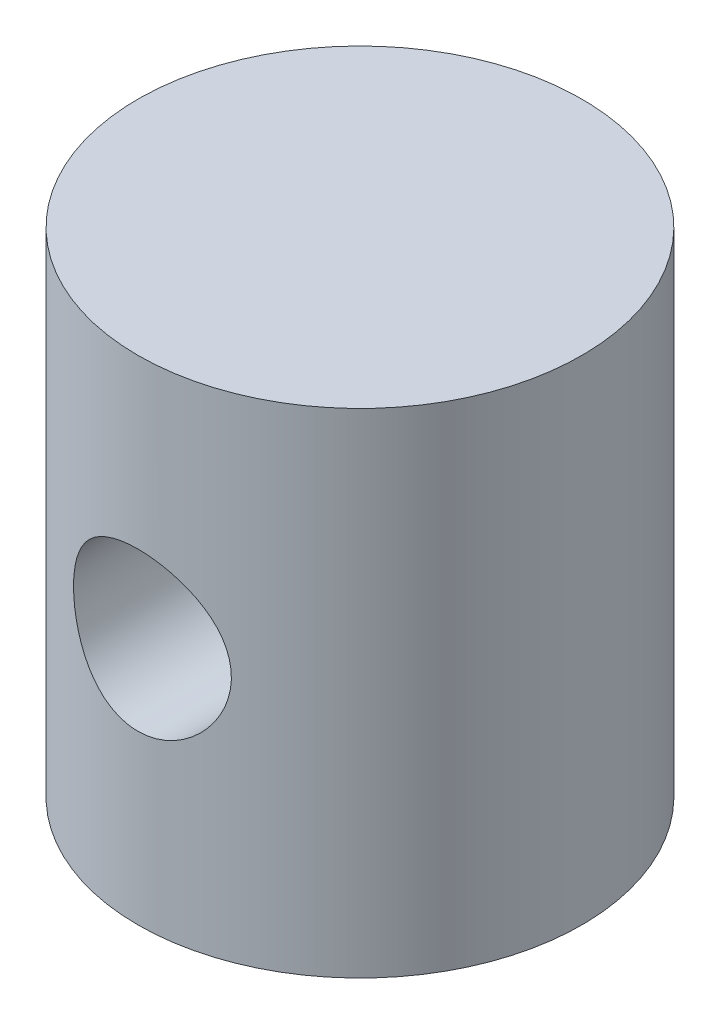
SolidWorks part; units mm, degrees
ref_plane "Front Plane" through (0, 0, 0) normal (0, 0, 1) x (1, 0, 0)
ref_plane "Top Plane" through (0, 0, 0) normal (0, 1, 0) x (1, 0, 0)
ref_plane "Right Plane" through (0, 0, 0) normal (1, 0, 0) x (0, 0, -1)
sketch "Sketch3" plane through (0, 0, 0) normal (0, 1, 0) x (1, 0, 0)
  circle A0 centre (0, 0) radius 4.5
  dimension "D1" = 9
extrude "Boss-Extrude1" add sketch "Sketch3" along normal blind 10
sketch "Sketch4" plane through (0, 0, 0) normal (0, 0, 1) x (1, 0, 0)
  line L0 (-4.5, 5) -> (-1.6, 5)
  line L1 (-4.5, 10) -> (-4.5, 0) construction
  line L2 (4.5, 0) -> (4.5, 10) construction
  line L3 (1.6, 5) -> (4.5, 5)
  circle A0 centre (0, 5) radius 1.6
  dimension "D1" = 3.2
extrude "Cut-Extrude1" cut sketch "Sketch4" against normal blind 10 contours A0
sketch "Sketch9" plane through (0, 0, 0) normal (0, 0, 1) x (1, 0, 0)
  circle A0 centre (0, 5) radius 1.6
extrude "Cut-Extrude2" cut sketch "Sketch9" along normal blind 49
